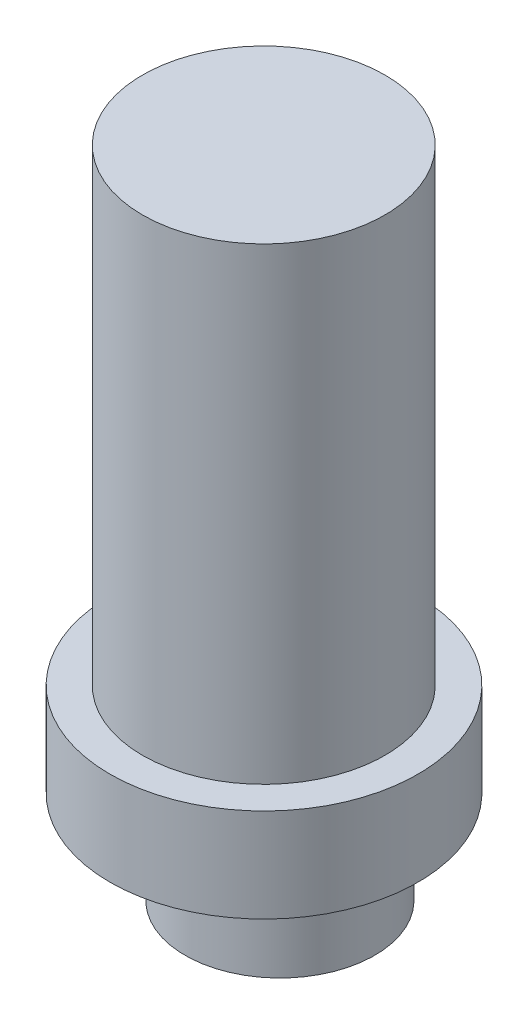
SolidWorks part; units mm, degrees
ref_plane "Front Plane" through (0, 0, 0) normal (0, 0, 1) x (1, 0, 0)
ref_plane "Top Plane" through (0, 0, 0) normal (0, 1, 0) x (1, 0, 0)
ref_plane "Right Plane" through (0, 0, 0) normal (1, 0, 0) x (0, 0, -1)
sketch "Sketch1" plane through (0, 0, 0) normal (0, 1, 0) x (1, 0, 0)
  circle A0 centre (0, 1.8009) radius 16.4579
extrude "Boss-Extrude1" add sketch "Sketch1" along normal blind 10
sketch "Sketch2" plane through (0, 10, 0) normal (0, 1, 0) x (1, 0, 0)
  circle A0 centre (0, 1.7734) radius 12.9535
extrude "Boss-Extrude2" add sketch "Sketch2" along normal blind 50
sketch "Sketch3" plane through (0, 0, 0) normal (0, -1, 0) x (-1, 0, 0)
  circle A0 centre (-0.78, 2.7185) radius 10.1301
extrude "Boss-Extrude3" add sketch "Sketch3" along normal blind 10
